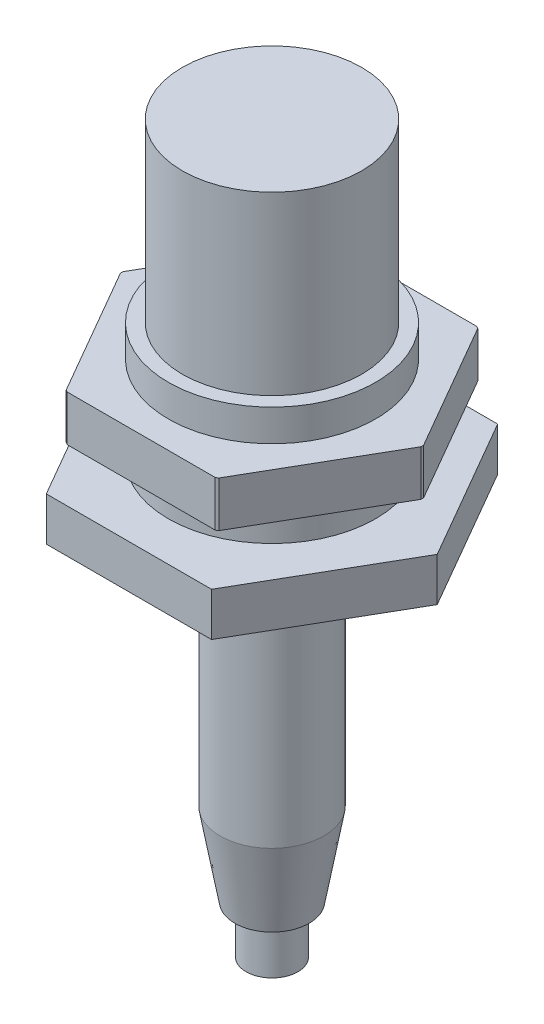
SolidWorks part; units mm, degrees
ref_plane "Front" through (0, 0, 0) normal (0, 0, 1) x (1, 0, 0)
ref_plane "Top" through (0, 0, 0) normal (0, 1, 0) x (1, 0, 0)
ref_plane "Right" through (0, 0, 0) normal (1, 0, 0) x (0, 0, -1)
sketch "Sketch1" plane through (0, 0, 0) normal (0, 0, 1) x (1, 0, 0)
  line L0 (0, 42.2586) -> (0, -42.2586) construction
  line L1 (1.5875, -26.416) -> (1.5875, -23.495)
  line L2 (5.2705, -2.667) -> (10.1219, -2.667)
  line L3 (10.1219, -2.667) -> (10.1219, 0)
  line L4 (10.1219, 0) -> (6.35, 0)
  line L5 (6.35, 0) -> (6.35, 2.5)
  line L6 (5.4928, 7.239) -> (6.35, 7.239)
  line L7 (5.2705, -2.667) -> (5.2705, -4.445)
  line L8 (5.2705, -4.445) -> (3.175, -4.445)
  line L9 (5.4928, 7.239) -> (5.4928, 18.034)
  line L10 (5.4928, 18.034) -> (0, 18.034)
  line L11 (0, 18.034) -> (0, -26.416)
  line L12 (0, -26.416) -> (1.5875, -26.416)
  line L13 (3.175, -4.445) -> (3.175, -23.495)
  line L14 (3.175, -23.495) -> (1.5875, -23.495)
  line L15 (6.35, 2.5) -> (9.2075, 2.5)
  line L16 (9.2075, 2.5) -> (9.2075, 5.294)
  line L17 (9.2075, 5.294) -> (6.35, 5.294)
  line L18 (6.35, 5.294) -> (6.35, 7.239)
  dimension "D1" = 12.7
  dimension "D2" = 10.795
  dimension "D3" = 3.175
  dimension "D4" = 7.239
  dimension "D5" = 20.2438
  dimension "D6" = 2.667
  dimension "D7" = 44.45
  dimension "D8" = 6.35
  dimension "D9" = 10.9855
  dimension "D10" = 1.778
  dimension "D11" = 10.541
  dimension "D12" = 19.05
  dimension "D13" = 2.5
  dimension "D14" = 2.794
  dimension "D15" = 18.415
revolve "Revolve1" add sketch "Sketch1" angle 360 about L0
sketch "Sketch2" plane through (0, -2.667, 0) normal (0, -1, 0) x (1, 0, 0)
  line L0 (-5.0609, 8.7658) -> (5.0609, 8.7658)
  line L1 (5.0609, 8.7658) -> (10.1219, 0)
  line L2 (10.1219, 0) -> (5.0609, -8.7658)
  line L3 (5.0609, -8.7658) -> (-5.0609, -8.7658)
  line L4 (-5.0609, -8.7658) -> (-10.1219, 0)
  line L5 (-10.1219, 0) -> (-5.0609, 8.7658)
  circle A0 centre (0, 0) radius 10.1219 construction
extrude "Cut-Extrude1" cut sketch "Sketch2" against normal up to surface (2.667 mm away) flip side to cut up to face at (-6.35, 0, 0)
chamfer "Chamfer1" distance 5.08 angle 10 1 edges at (-3.175, -23.495, 0)
sketch "Sketch3" plane through (0, 5.294, 0) normal (0, 1, 0) x (1, 0, 0)
  line L1 (4.6267, -8.0137) -> (9.2534, 0)
  line L2 (9.2534, 0) -> (4.6267, 8.0137)
  line L3 (4.6267, 8.0137) -> (-4.6267, 8.0137)
  line L4 (-4.6267, 8.0137) -> (-9.2534, 0)
  line L5 (-9.2534, 0) -> (-4.6267, -8.0137)
  line L6 (-4.6267, -8.0137) -> (4.6267, -8.0137)
  circle A0 centre (0, 0) radius 8.0137 construction
  dimension "D1" = 16.0274
extrude "Cut-Extrude2" cut sketch "Sketch3" against normal up to surface (2.794 mm away) flip side to cut up to face at (-9.2075, 2.5, 0)
sketch "Sketch4" plane through (0, 0, 0) normal (0, 1, 0) x (1, 0, 0)
  line L0 (-3.341, 5.4) -> (3.341, 5.4)
  line L1 (0, 0) -> (0, 5.4) construction
  circle A0 centre (0, 0) radius 6.35 construction
  arc A1 (3.341, 5.4) -> (-3.341, 5.4) centre (0, 0) ccw
  dimension "D1" = 11.75
extrude "Cut-Extrude3" cut sketch "Sketch4" along normal up to surface (2.5 mm away) up to face at (-6.35, 2.5, 0)
